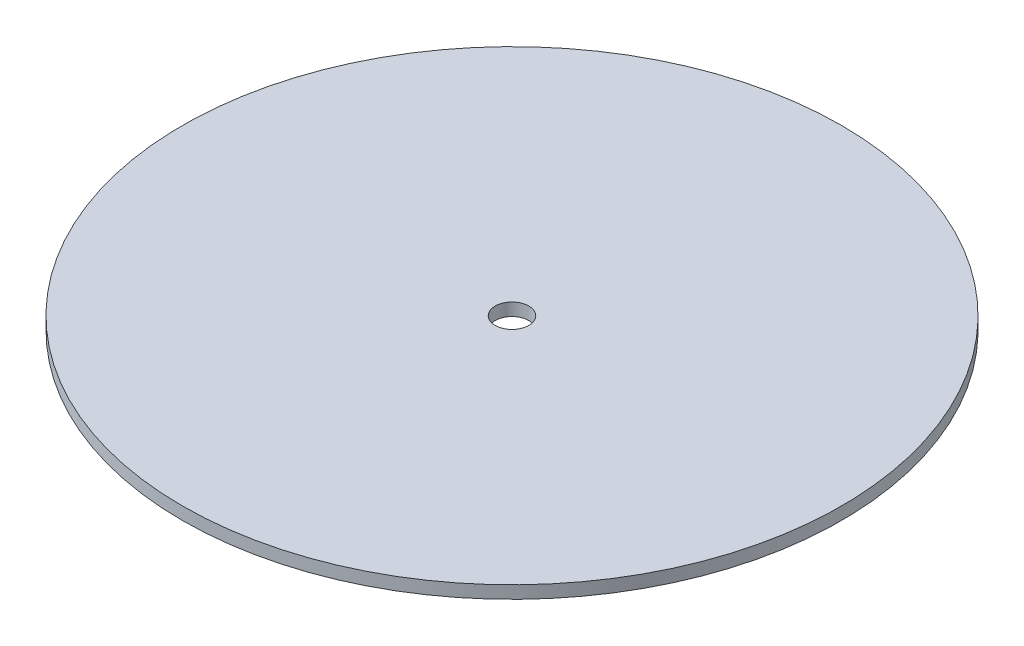
SolidWorks part; units mm, degrees
material "1060 Alloy"
ref_plane "Front Plane" through (0, 0, 0) normal (0, 0, 1) x (1, 0, 0)
ref_plane "Top Plane" through (0, 0, 0) normal (0, 1, 0) x (1, 0, 0)
ref_plane "Right Plane" through (0, 0, 0) normal (1, 0, 0) x (0, 0, -1)
sketch "Sketch1" plane through (0, 0, 0) normal (0, 1, 0) x (1, 0, 0)
  circle A0 centre (0, 0) radius 78.35
  circle A1 centre (0, 0) radius 4
  dimension "D1" = 156.7
  dimension "D2" = 8
extrude "Boss-Extrude1" add sketch "Sketch1" along normal blind 3
